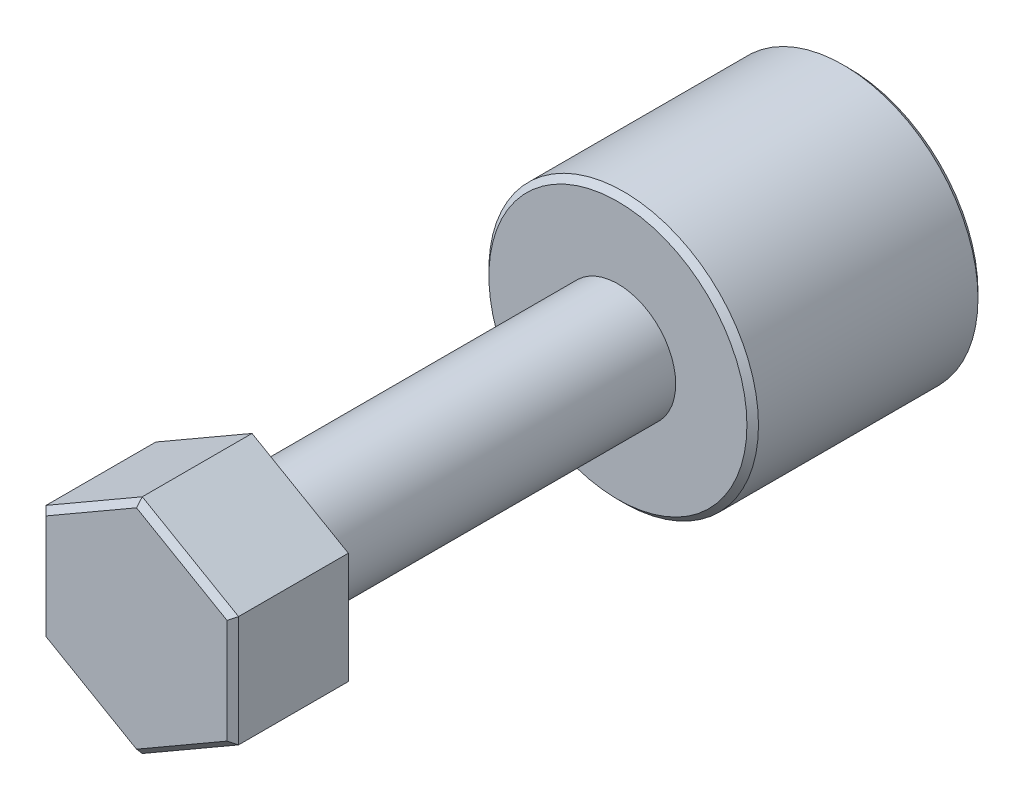
SolidWorks part; units mm, degrees
ref_plane "前视基准面" through (0, 0, 0) normal (0, 0, 1) x (1, 0, 0)
ref_plane "上视基准面" through (0, 0, 0) normal (0, 1, 0) x (1, 0, 0)
ref_plane "右视基准面" through (0, 0, 0) normal (1, 0, 0) x (0, 0, -1)
sketch "草图1" plane through (0, 0, 0) normal (0, 0, 1) x (1, 0, 0)
  circle A0 centre (0, 0) radius 7
  dimension "D1" = 14
extrude "凸台-拉伸1" add sketch "草图1" along normal blind 12
sketch "草图2" plane through (0, 0, 12) normal (0, 0, 1) x (1, 0, 0)
  circle A0 centre (0, 0) radius 3
  dimension "D1" = 6
extrude "凸台-拉伸2" add sketch "草图2" along normal blind 25
sketch "草图3" plane through (0, 0, 37) normal (0, 0, 1) x (1, 0, 0)
  line L0 (0, 0) -> (0, 5.7735) construction
  line L1 (5, 2.8868) -> (0, 5.7735)
  line L2 (0, 5.7735) -> (-5, 2.8868)
  line L3 (-5, 2.8868) -> (-5, -2.8868)
  line L4 (-5, -2.8868) -> (0, -5.7735)
  line L5 (0, -5.7735) -> (5, -2.8868)
  line L6 (5, -2.8868) -> (5, 2.8868)
  circle A0 centre (0, 0) radius 5 construction
  dimension "D1" = 10
extrude "凸台-拉伸3" add sketch "草图3" against normal blind 6
chamfer "倒角1" distance 0.3 angle 45 8 edges at (2.5, -4.3301, 37) (-2.5, -4.3301, 37) (-5, 0, 37) (-2.5, 4.3301, 37) (2.5, 4.3301, 37) (5, 0, 37) (7, 0, 0) (7, 0, 12)
